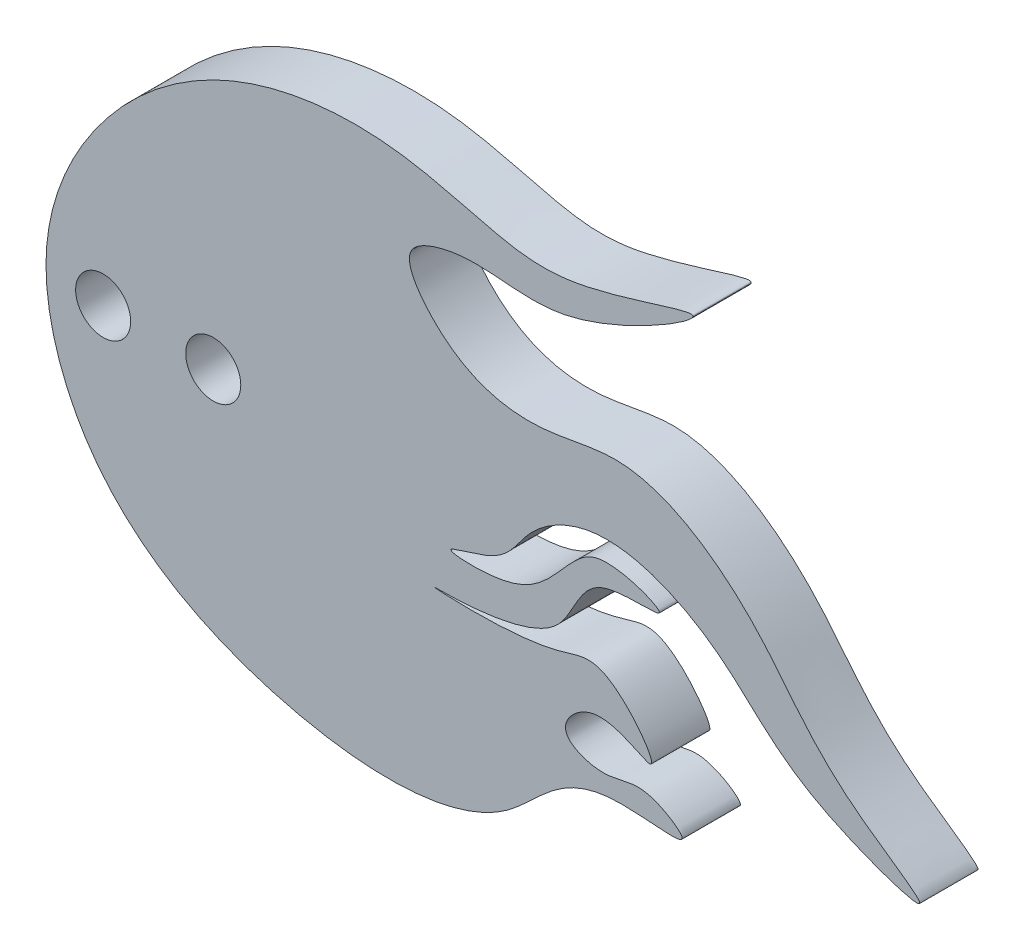
SolidWorks part; units mm, degrees
ref_plane "前视基准面" through (0, 0, 0) normal (0, 0, 1) x (1, 0, 0)
ref_plane "上视基准面" through (0, 0, 0) normal (0, 1, 0) x (1, 0, 0)
ref_plane "右视基准面" through (0, 0, 0) normal (1, 0, 0) x (0, 0, -1)
sketch "Sketch1" plane through (0, 0, 0) normal (0, 0, 1) x (1, 0, 0)
  line L0 (125.0813, 142.4115) -> (125.0813, 99.0768) construction
  line L1 (0, 0) -> (0, 22.8) construction
  line L2 (0, 22.8) -> (26.2914, 22.8) construction
  dimension "D1" = 22.8
sketch "Sketch2" plane through (0, 0, 0) normal (0, 0, 1) x (1, 0, 0)
  line L0 (0, 22.8) -> (26.2914, 22.8) construction
  spline S0 degree 3 poles (40.1959, 39.4826) (29.6714, 35.1045) (24.9195, 36.017) (18.6753, 37.787) (10.5215, 36.7204) (3.4189, 30.8704) (-0.131, 22.8337) (3.0321, 12.8046) (13.1318, 7.1081) (25.668, 6.7213) (29.4961, 13.3666) (37.1489, 11.7426) (33.3021, 14.1945) (31.4936, 13.0334) (28.3006, 14.1847) (31.0102, 16.9647) (35.5425, 13.4421) (31.46, 19.1265) (27.7324, 17.1992) (17.6518, 17.7981) (29.6014, 17.3321) (29.8804, 22.8702) (36.3581, 21.9797) (31.3765, 23.9854) (28.8257, 22.0406) (27.5941, 19.3932) (21.3586, 19.6805) (25.9109, 20.4768) (27.0474, 22.9379) (31.4, 25.5815) (38.1635, 22.4672) (41.2184, 18.0012) (51.0253, 14.6558) (42.9052, 19.5999) (40.2832, 24.4995) (33.5758, 29.4181) (27.2854, 27.5251) (22.8677, 28.5374) (19.903, 32.8524) (24.3998, 34.617) (28.5805, 32.4213) (40.1959, 39.4826) (29.6714, 35.1045) (24.9195, 36.017) knots -0.099064 -0.068215 -0.032739 0 0.019314 0.041091 0.08696 0.126254 0.163181 0.201008 0.258577 0.315726 0.345347 0.362814 0.373276 0.384074 0.394324 0.404233 0.418957 0.437984 0.449078 0.479473 0.510297 0.528972 0.543032 0.559124 0.565021 0.587262 0.60096 0.612435 0.624782 0.640444 0.676051 0.708185 0.73471 0.754186 0.7916 0.830668 0.849067 0.878547 0.892075 0.900936 0.931785 0.967261 1 1.019314 1.041091 1.08696 only from (29.2077, 35.7175) to (29.2077, 35.7175)
  point P1 (32.0708, 28.5345)
  point P3 (39.5347, 24.4293)
  point P5 (28.09, 28.0369)
extrude "Boss-Extrude1" add sketch "Sketch2" along normal blind 3.175
sketch "Sketch3" plane through (0, 0, 3.175) normal (0, 0, 1) x (1, 0, 0)
  line L0 (4, 21.8382) -> (17.9347, 21.8382) construction
  circle A0 centre (4, 21.8382) radius 1.5
  circle A1 centre (10, 21.8382) radius 1.5
  dimension "D1" = 3
  dimension "D3" = 3
  dimension "D2" = 4
  dimension "D4" = 6
extrude "Cut-Extrude1" cut sketch "Sketch3" against normal through all
